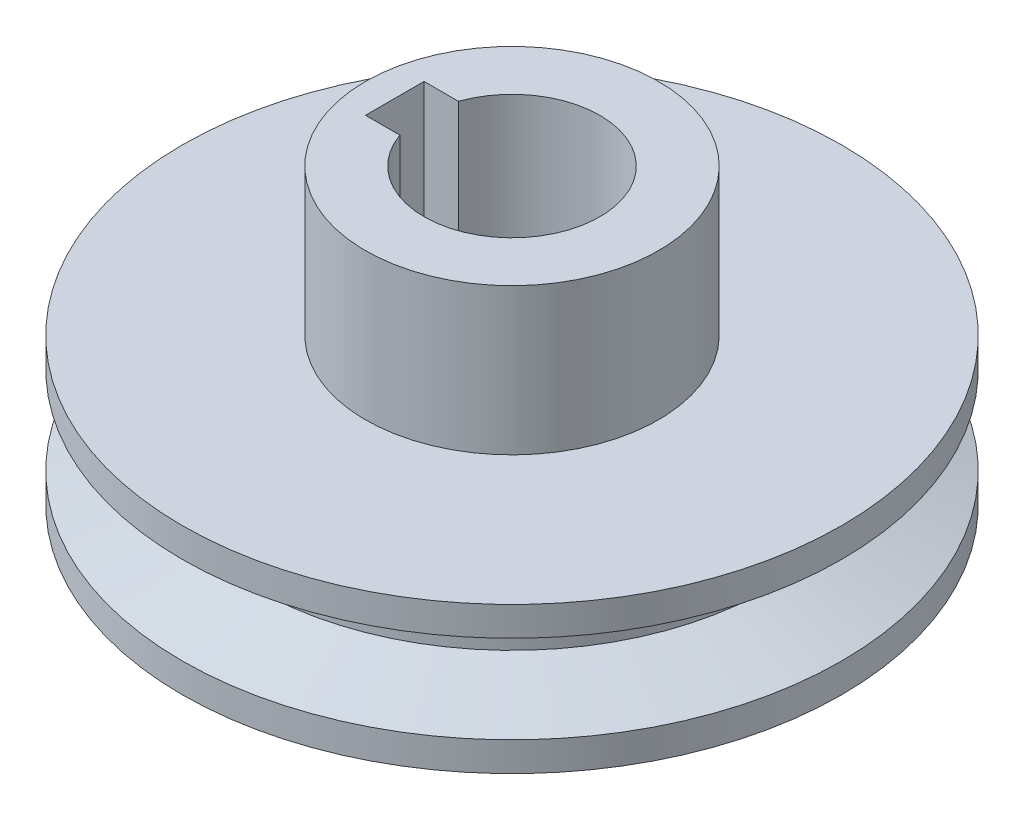
SolidWorks part; units mm, degrees
ref_plane "Front Plane" through (0, 0, 0) normal (0, 0, 1) x (1, 0, 0)
ref_plane "Top Plane" through (0, 0, 0) normal (0, 1, 0) x (1, 0, 0)
ref_plane "Right Plane" through (0, 0, 0) normal (1, 0, 0) x (0, 0, -1)
sketch "Sketch1" plane through (0, 0, 0) normal (0, 0, 1) x (1, 0, 0)
  line L0 (-12.5, 2.5) -> (-12.5, -2.5)
  line L1 (2.5, 10) -> (-22.5, 10)
  line L2 (22.5, 10) -> (22.5, -10)
  line L3 (22.5, -10) -> (-22.5, -10)
  line L4 (-22.5, 10) -> (-22.5, 6)
  line L5 (22.5, 10) -> (-22.5, -10) construction
  line L6 (22.5, -10) -> (-22.5, 10) construction
  line L7 (-22.5, 6) -> (-12.5, 2.5)
  line L8 (-12.5, -2.5) -> (-22.5, -6)
  line L9 (-22.5, -6) -> (-22.5, -10)
  line L10 (2.5, 10) -> (2.5, 30)
  line L11 (2.5, 30) -> (22.5, 30)
  line L12 (22.5, 30) -> (22.5, 10)
  line L13 (22.5, 43.9563) -> (22.5, -17.8182) construction
  point P0 (0, 0)
  dimension "D1" = 45
  dimension "D2" = 20
  dimension "D3" = 10
  dimension "D4" = 5
  dimension "D6" = 4
  dimension "D7" = 4
  dimension "D8" = 20
  dimension "D9" = 20
revolve "Revolve1" add sketch "Sketch1" angle 360 about L13
sketch "Sketch2" plane through (0, 30, 0) normal (0, 1, 0) x (1, 0, 0)
  circle A0 centre (22.5, 0) radius 12
extrude "Cut-Extrude1" cut sketch "Sketch2" against normal through all
sketch "Sketch3" plane through (0, 30, 0) normal (0, 1, 0) x (1, 0, 0)
  line L0 (22.5, 4) -> (22.5, -4)
  line L1 (22.5, -4) -> (6.5, -4)
  line L3 (22.5, 4) -> (6.5, 4)
  line L4 (6.5, -4) -> (6.5, 4)
  line L5 (22.5, 0) -> (6.5, 4) construction
  line L6 (22.5, 0) -> (6.5, -4) construction
  point P0 (22.5, 0)
  dimension "D1" = 8
extrude "Cut-Extrude2" cut sketch "Sketch3" against normal through all
